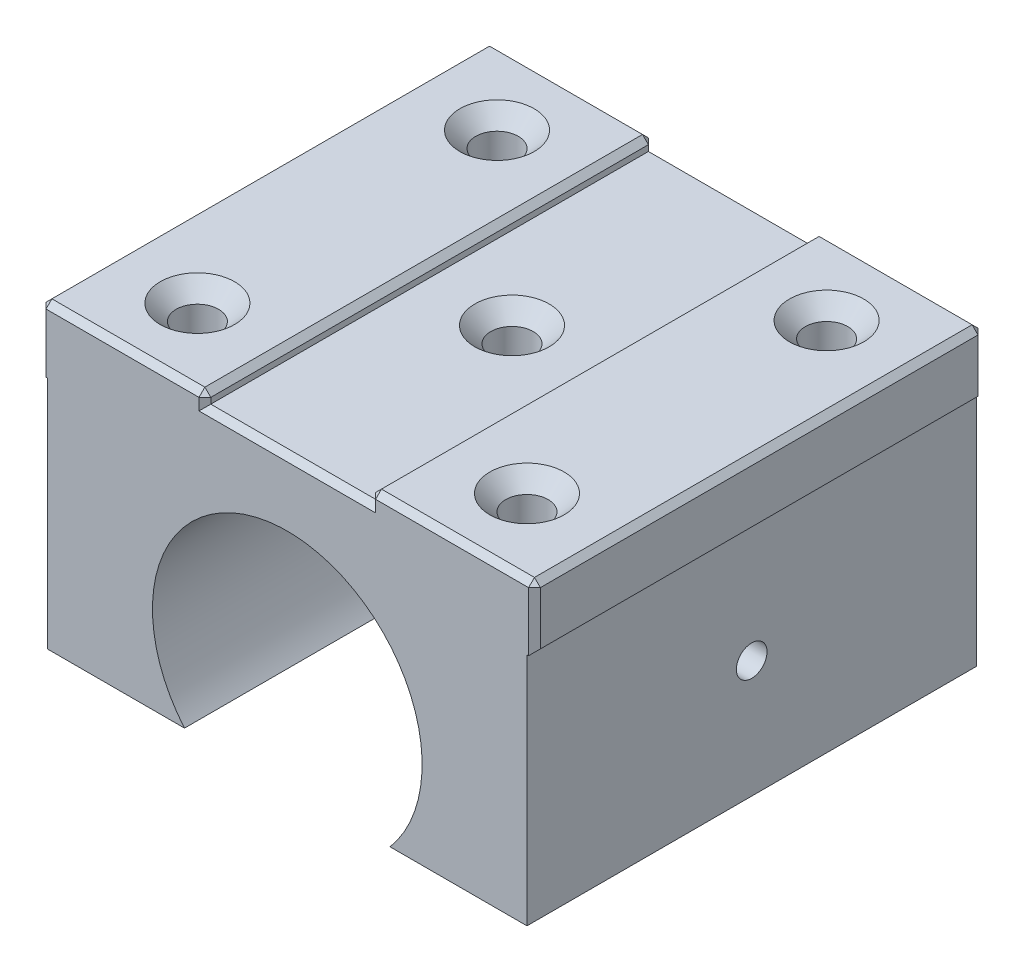
SolidWorks part; units mm, degrees
ref_plane "Front Plane" through (0, 0, 0) normal (0, 0, 1) x (1, 0, 0)
ref_plane "Top Plane" through (0, 0, 0) normal (0, 1, 0) x (1, 0, 0)
ref_plane "Right Plane" through (0, 0, 0) normal (1, 0, 0) x (0, 0, -1)
sketch "Sketch1" plane through (0, 0, 0) normal (0, 0, 1) x (1, 0, 0)
  line L0 (0, 0) -> (0, 11.43) construction
  line L1 (-20.32, -7.3995) -> (-8.7116, -7.3995)
  line L2 (-20.32, -7.3995) -> (-20.32, 12.5005)
  line L3 (-20.955, 18.0005) -> (20.955, 18.0005)
  line L4 (20.32, -7.3995) -> (20.32, 12.5005)
  line L5 (8.7116, -7.3995) -> (20.32, -7.3995)
  line L6 (20.32, 12.5005) -> (20.955, 12.5005)
  line L7 (-20.955, 18.0005) -> (20.955, 18.0005)
  line L8 (-20.955, 18.0005) -> (-20.955, 12.5005)
  line L9 (-20.955, 12.5005) -> (-20.32, 12.5005)
  line L10 (20.955, 18.0005) -> (20.955, 12.5005)
  line L11 (0, 18.0005) -> (0, 51.8376) construction
  line L13 (-20.955, 18.0005) -> (20.955, 18.0005)
  arc A0 (8.7116, -7.3995) -> (-8.7116, -7.3995) centre (0, 0) ccw
  point P4 (0, 0)
  point P5 (22.1396, 18.0005)
  point P14 (-23.2767, 18.0005)
  dimension "D1" = 22.86
  dimension "D2" = 25.4
  dimension "D3" = 40.64
  dimension "D4" = 18.0005
  dimension "D5" = 5.5
  dimension "D6" = 41.91
extrude "Boss-Extrude1" add sketch "Sketch1" along normal blind 38.1 contours A0 L0 L3 L8 L9 L2 L1 | L0 A0 L5 L4 L6 L10 L7
sketch "Sketch3" plane through (0, 18.0005, 0) normal (0, 1, 0) x (1, 0, 0)
  line L0 (0, 0) -> (0, -38.1) construction
  line L1 (-20.955, 0) -> (20.955, 0) construction
  line L2 (-20.955, -38.1) -> (20.955, -38.1) construction
  line L3 (-20.955, -19.05) -> (20.955, -19.05) construction
  line L4 (-20.955, -38.1) -> (-20.955, 0) construction
  line L5 (20.955, -38.1) -> (20.955, 0) construction
  line L6 (-13.97, -6.35) -> (-13.97, -31.75) construction
  line L7 (-6.985, 0) -> (-6.985, -38.1) construction
  line L8 (6.985, 0) -> (6.985, -38.1) construction
  line L11 (20.955, 0) -> (-20.955, 0)
  line L12 (-20.955, 0) -> (-20.955, -38.1)
  line L13 (-20.955, -38.1) -> (20.955, -38.1)
  line L14 (20.955, -38.1) -> (20.955, 0)
  line L15 (20.955, 0) -> (-20.955, 0) construction
  line L16 (-20.955, 0) -> (-20.955, -38.1) construction
  line L17 (-20.955, -38.1) -> (20.955, -38.1) construction
  line L18 (20.955, -38.1) -> (20.955, 0) construction
  circle A0 centre (-13.97, -6.35) radius 1
  circle A1 centre (13.97, -6.35) radius 1
  circle A2 centre (-13.97, -31.75) radius 1
  circle A3 centre (13.97, -31.75) radius 1
  circle A4 centre (0, -19.05) radius 1
  dimension "D3" = 2
  dimension "D4" = 2
  dimension "D1" = 27.94
  dimension "D2" = 25.4
  dimension "D5" = 0
sketch "Sketch4" plane through (0, 0, 38.1) normal (0, 0, 1) x (1, 0, 0)
  line L0 (-6.985, 18.0005) -> (-6.985, 17.0005)
  line L1 (-6.985, 17.0005) -> (6.985, 17.0005)
  line L2 (6.985, 17.0005) -> (6.985, 18.0005)
  dimension "D1" = 1
sketch "Sketch9" plane through (0, 18.0005, 0) normal (0, 1, 0) x (1, 0, 0)
  point P0 (-13.97, -6.35)
  point P3 (-13.97, -31.75)
  point P6 (13.97, -31.75)
  point P9 (13.97, -6.35)
hole_wizard "CSK for M3 Countersunk Flat Head Screw2" positions "Sketch9" profile "Sketch8" countersink size "M3" standard "ISO"
sketch "Sketch8" plane through (-13.97, 18.0005, 6.35) normal (1, 0, 0) x (0, 0, 1)
  line L0 (0, 0) -> (0, 11.0815)
  line L1 (0, 11.0815) -> (1.8, 10)
  line L2 (1.8, 10) -> (1.8, 1.35)
  line L3 (1.8, 1.35) -> (3.15, 0)
  line L5 (3.15, 0) -> (0, 0)
  line L6 (-1.8, 1.35) -> (-3.15, 0) construction
  line L10 (0, 11.0815) -> (-1.8, 10) construction
  line L11 (0, -6.35) -> (0, 107.95) construction
  dimension "Hole Dia." = 3.6
  dimension "Hole Depth" = 10
  dimension "Near C'Sink Dia." = 6.3
  dimension "Near C'Sink Angle" = 90
  dimension "Drill Angle" = 118
extrude "Cut-Extrude1" cut sketch "Sketch4" against normal through all and the other way through all
sketch "Sketch11" plane through (0, 17.0005, 0) normal (0, 1, 0) x (1, 0, 0)
  circle A0 centre (0, -19.05) radius 1 construction
  circle A1 centre (0, -19.05) radius 1
  point P2 (0, -19.05)
hole_wizard "CSK for M3 Countersunk Flat Head Screw3" positions "Sketch11" profile "Sketch12" countersink size "M3" standard "ISO"
sketch "Sketch12" plane through (0, 17.0005, 19.05) normal (1, 0, 0) x (0, 0, 1)
  line L0 (0, 0) -> (0, 11.0815)
  line L1 (0, 11.0815) -> (1.8, 10)
  line L2 (1.8, 10) -> (1.8, 1.35)
  line L3 (1.8, 1.35) -> (3.15, 0)
  line L5 (3.15, 0) -> (0, 0)
  line L6 (-1.8, 1.35) -> (-3.15, 0) construction
  line L10 (0, 11.0815) -> (-1.8, 10) construction
  line L11 (0, -6.35) -> (0, 107.95) construction
  dimension "Hole Dia." = 3.6
  dimension "Hole Depth" = 10
  dimension "Near C'Sink Dia." = 6.3
  dimension "Near C'Sink Angle" = 90
  dimension "Drill Angle" = 118
chamfer "Chamfer1" distance 0.5 angle 45 20 edges at (20.955, 12.5005, 19.05) (13.97, 18.0005, 0) (13.97, 18.0005, 38.1) (20.955, 15.2505, 0) (20.955, 15.2505, 38.1) (6.985, 17.5005, 38.1) (6.985, 17.5005, 0) (20.955, 18.0005, 19.05) (6.985, 18.0005, 19.05) (-6.985, 17.5005, 38.1) (-6.985, 17.5005, 0) (-13.97, 18.0005, 0) (-13.97, 18.0005, 38.1) (-6.985, 18.0005, 19.05) (-20.955, 18.0005, 19.05) (-20.955, 12.5005, 19.05) (0, 17.0005, 38.1) (0, 17.0005, 0) (-20.955, 15.2505, 0) (-20.955, 15.2505, 38.1)
sketch "Sketch13" plane through (-20.32, 0, 0) normal (-1, 0, 0) x (0, 0, 1)
  line L0 (0, 12.5005) -> (38.1, -7.3995) construction
  line L1 (0, -7.3995) -> (38.1, 12.5005) construction
  point P10 (19.05, 2.5505)
hole_wizard "CSK for M2 Countersunk Flat Head Screw2" positions "Sketch13" profile "Sketch14" countersink size "M2" standard "ISO" end condition through all
sketch "Sketch14" plane through (-20.32, 2.5505, 19.05) normal (0, 1, 0) x (0, 0, 1)
  line L0 (0, 0) -> (0, 41.275)
  line L1 (0, 41.275) -> (1.3, 41.275)
  line L2 (1.3, 41.275) -> (1.3, 0.9)
  line L3 (1.3, 0.9) -> (2.2, 0)
  line L5 (2.2, 0) -> (0, 0)
  line L6 (-1.3, 0.9) -> (-2.2, 0) construction
  line L11 (0, -6.35) -> (0, 107.95) construction
  dimension "Thru Hole Dia." = 2.6
  dimension "Thru Hole Depth" = 41.275
  dimension "Near C'Sink Dia." = 4.4
  dimension "Near C'Sink Angle" = 90
ref_plane "Plane1" through (0, 0, 33.1) normal (0, 0, 1) x (1, 0, 0)
ref_plane "Plane2" through (0, 0, 19.05) normal (0, 0, 1) x (1, 0, 0)
ref_plane "Plane3" through (0, 0, 5) normal (0, 0, -1) x (-1, 0, 0)
sketch "Sketch16" plane through (0, 0, 33.1) normal (0, 0, 1) x (1, 0, 0)
  line L0 (-8.0822, 8.0822) -> (0, 0) construction
  line L1 (0, 0) -> (8.0822, 8.0822) construction
  line L2 (0, 0) -> (0, 11.43) construction
  line L3 (-7.3751, 7.3751) -> (-8.7893, 8.7893)
  arc A0 (8.7116, -7.3995) -> (-8.7116, -7.3995) centre (0, 0) ccw construction
  arc A1 (-7.3751, 7.3751) -> (-8.7893, 8.7893) centre (-8.0822, 8.0822) ccw
  dimension "D2" = 2
  dimension "D1" = 90
revolve "Revolve4" add sketch "Sketch16" angle 360 about L0
mirror "Mirror1" about plane through (0, 0, 0) normal (1, 0, 0) of "Revolve4"
pattern_linear "LPattern1" count 10 spacing 3.1222 along (0, 0, -1) of "Mirror1", "Revolve4"
